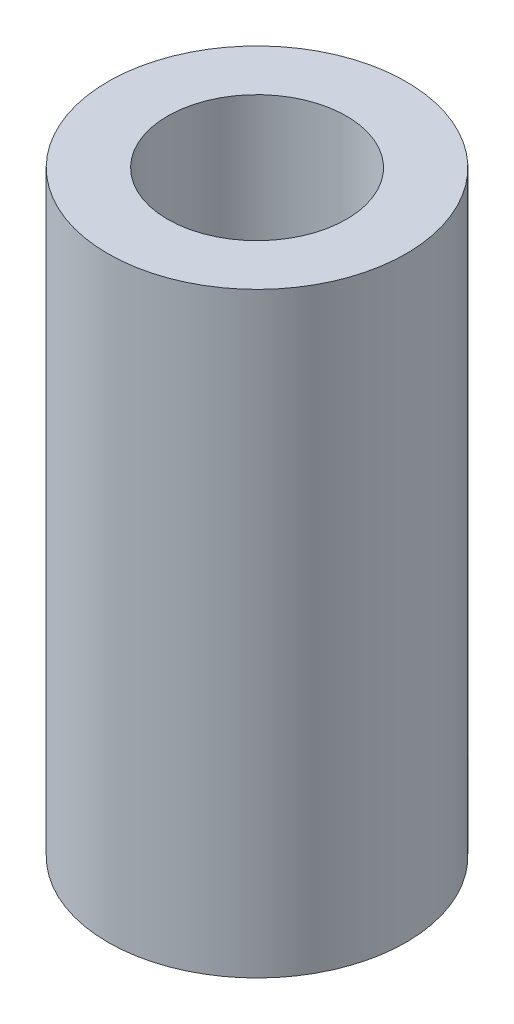
SolidWorks part; units mm, degrees
ref_plane "Front Plane" through (0, 0, 0) normal (0, 0, 1) x (1, 0, 0)
ref_plane "Top Plane" through (0, 0, 0) normal (0, 1, 0) x (1, 0, 0)
ref_plane "Right Plane" through (0, 0, 0) normal (1, 0, 0) x (0, 0, -1)
sketch "Sketch1" plane through (0, 0, 0) normal (0, 1, 0) x (1, 0, 0)
  circle A0 centre (0, 0) radius 2.5
  dimension "D1" = 5
extrude "Boss-Extrude1" add sketch "Sketch1" along normal blind 10
sketch "Sketch2" plane through (0, 10, 0) normal (0, 1, 0) x (1, 0, 0)
  circle A0 centre (0, 0) radius 1.5
  dimension "D1" = 3
extrude "Cut-Extrude1" cut sketch "Sketch2" against normal blind 16
